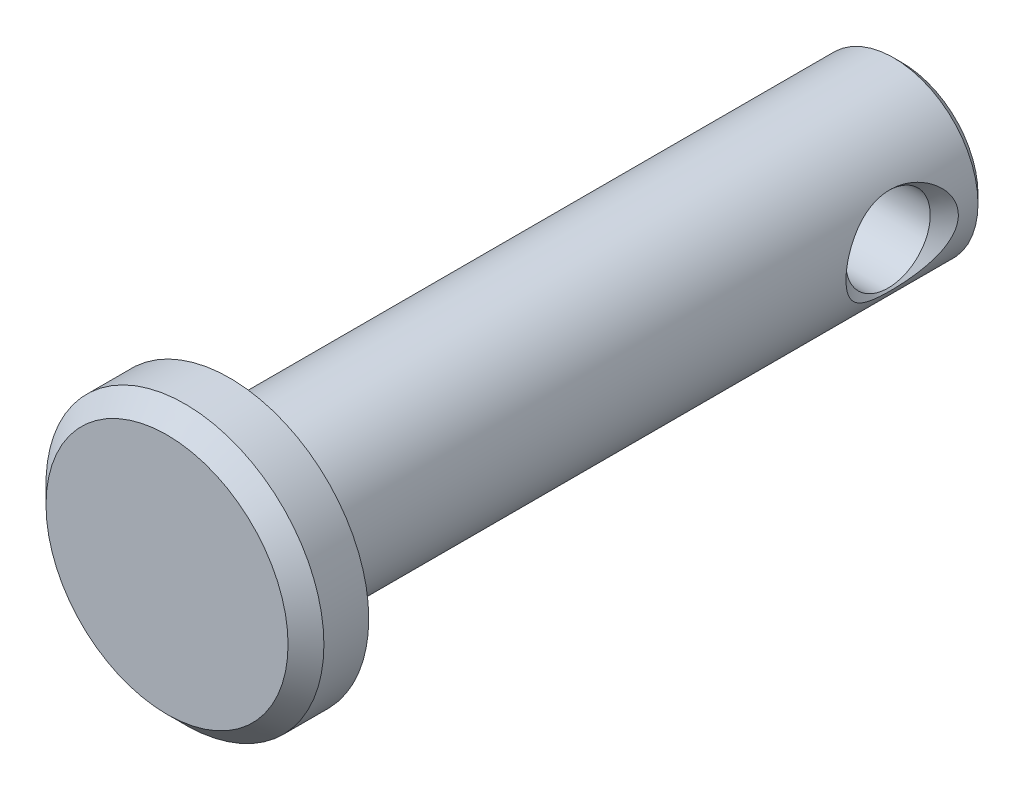
SolidWorks part; units mm, degrees
ref_plane "Front Plane" through (0, 0, 0) normal (0, 0, 1) x (1, 0, 0)
ref_plane "Top Plane" through (0, 0, 0) normal (0, 1, 0) x (1, 0, 0)
ref_plane "Right Plane" through (0, 0, 0) normal (1, 0, 0) x (0, 0, -1)
sketch "Sketch1" plane through (0, 0, 0) normal (1, 0, 0) x (0, 0, -1)
  line L0 (-10.414, 0) -> (10.414, 0) construction
  line L1 (10.414, 2.3876) -> (10.414, -2.3876) construction
  line L2 (-8.636, 3.937) -> (-8.636, -3.937) construction
  line L3 (-10.414, 3.937) -> (-10.414, -3.937) construction
  line L4 (-10.414, -3.429) -> (-9.906, -3.937) construction
  line L5 (-9.906, -3.937) -> (-8.636, -3.937) construction
  line L6 (-10.414, -3.937) -> (-9.906, -3.937) construction
  line L9 (7.1823, 0.8441) -> (8.8705, -0.8441) construction
  line L11 (7.1823, -0.8441) -> (8.8705, 0.8441) construction
  circle A0 centre (8.0264, 0) radius 1.1938
  circle A1 centre (8.0264, 0) radius 0.8001
  point P11 (-8.636, 0)
  dimension "Through Hole Diameter" = 2.3876
  dimension "For Maximum Cotter Pin Diameter" = 1.6002
  dimension "Usable Length" = 15.4686
  dimension "Length" = 19.05
  dimension "Diameter" = 4.7752
  dimension "Head Diameter" = 7.874
  dimension "Head Height" = 1.778
  dimension "L" = 45
  dimension "D" = 0.508
sketch "Sketch2" plane through (0, 0, 0) normal (1, 0, 0) x (0, 0, -1)
  line L0 (10.1752, 2.3876) -> (-8.5166, 2.3876)
  line L1 (-8.636, 3.937) -> (-8.636, -3.937) construction
  line L2 (-8.636, 2.507) -> (-8.636, 3.937)
  line L3 (-8.636, 3.937) -> (-9.906, 3.937)
  line L4 (-10.414, 3.429) -> (-10.414, 0)
  line L5 (-10.414, 0) -> (10.414, 0)
  line L6 (10.414, 0) -> (10.414, 2.1488)
  line L7 (10.414, -2.3876) -> (10.0161, -2.3876) construction
  line L8 (10.0161, -2.3876) -> (9.6181, -2.3876) construction
  line L9 (9.6181, -2.3876) -> (9.2202, -2.3876) construction
  line L10 (9.2202, -2.3876) -> (9.2202, 0) construction
  line L11 (10.1752, 2.3876) -> (10.414, 2.1488)
  line L12 (-9.906, 3.937) -> (-10.414, 3.429)
  line L13 (-10.414, 3.429) -> (-10.414, 3.937) construction
  line L14 (-10.414, 3.937) -> (-9.906, 3.937) construction
  line L16 (10.1752, 2.3876) -> (10.414, 2.3876) construction
  line L17 (10.414, 2.3876) -> (10.414, 2.1488) construction
  circle A0 centre (8.0264, 0) radius 1.1938 construction
  arc A1 (-8.5166, 2.3876) -> (-8.636, 2.507) centre (-8.5166, 2.507) cw
  point P24 (-8.636, 2.3876)
  dimension "D2" = 0.1194
  dimension "D1" = 0.2388
revolve "Revolve1" add sketch "Sketch2" angle 360 about L5
sketch "Sketch3" plane through (0, 0, 0) normal (1, 0, 0) x (0, 0, -1)
  circle A0 centre (8.0264, 0) radius 1.1938 construction
  circle A1 centre (8.0264, 0) radius 1.1938
extrude "Cut-Extrude1" cut sketch "Sketch3" against normal through all both and the other way through all
sketch "Sketch4" plane through (0, 0, 0) normal (0, 1, 0) x (1, 0, 0)
  line L0 (2.3876, 8.0264) -> (-2.3876, 8.0264) construction
  line L1 (2.3876, 6.4347) -> (0.7959, 8.0264)
  line L2 (2.3876, -8.5166) -> (2.3876, 6.8326) construction
  line L3 (0.7959, 8.0264) -> (2.3876, 8.0264)
  line L4 (2.3876, 8.0264) -> (2.3876, 6.4347)
  line L5 (0, 6.8326) -> (0, 9.2202) construction
  line L6 (0, 6.8326) -> (0, 9.2202) construction
  line L7 (-2.3876, 8.0264) -> (-2.3876, 6.4347)
  line L8 (-0.7959, 8.0264) -> (-2.3876, 8.0264)
  line L9 (-2.3876, 6.4347) -> (-0.7959, 8.0264)
  dimension "D1" = 45
  dimension "D2" = 3.1835
revolve "Cut-Revolve1" cut sketch "Sketch4" angle 360 about L0
equation "\"D1@Sketch2\"=\"Diameter@Sketch1\" * .05"
equation "\"D2@Sketch2\"=\"Diameter@Sketch1\" * .025"
equation "\"D2@Sketch4\"=\"Through Hole Diameter@Sketch1\" * 4/3"
